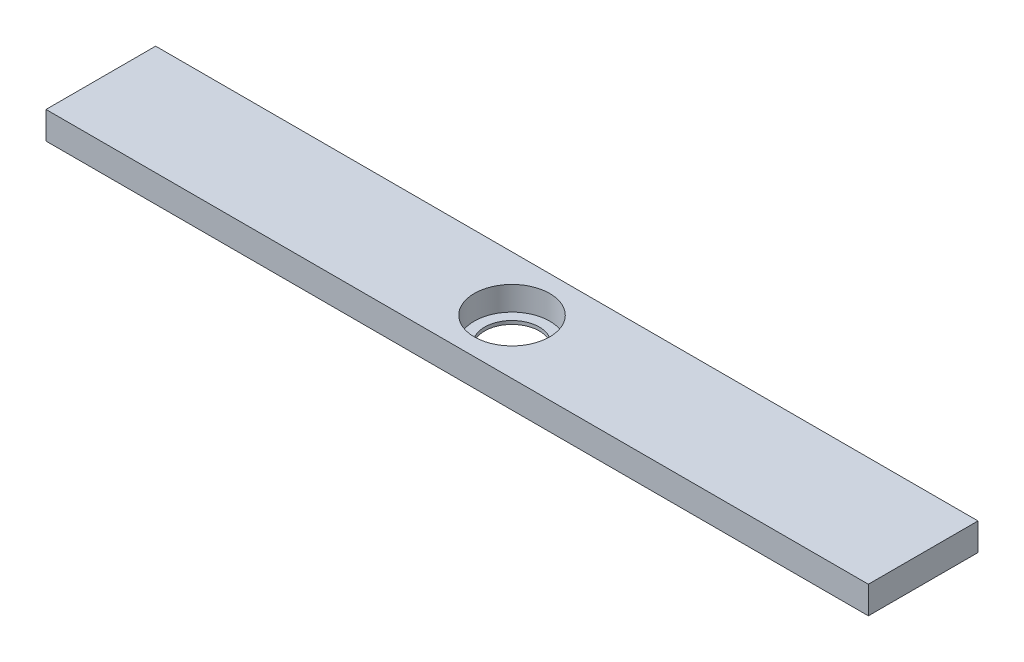
SolidWorks part; units mm, degrees
material "6061-T6 (SS)"
ref_plane "Front Plane" through (0, 0, 0) normal (0, 0, 1) x (1, 0, 0)
ref_plane "Top Plane" through (0, 0, 0) normal (0, 1, 0) x (1, 0, 0)
ref_plane "Right Plane" through (0, 0, 0) normal (1, 0, 0) x (0, 0, -1)
sketch "Sketch1" plane through (0, 0, 0) normal (0, 1, 0) x (1, 0, 0)
  line L1 (-190.5, -25.4) -> (190.5, -25.4)
  line L2 (-190.5, -25.4) -> (-190.5, 25.4)
  line L3 (-190.5, 25.4) -> (190.5, 25.4)
  line L4 (190.5, -25.4) -> (190.5, 25.4)
  line L5 (-190.5, -25.4) -> (190.5, 25.4) construction
  line L6 (-190.5, 25.4) -> (190.5, -25.4) construction
  point P0 (0, 0)
  dimension "D1" = 381
  dimension "D2" = 50.8
extrude "Boss-Extrude1" add sketch "Sketch1" along normal blind 12.7
sketch "Sketch2" plane through (0, 12.7, 0) normal (0, 1, 0) x (1, 0, 0)
  circle A0 centre (0, 0) radius 17.4625
  dimension "D1" = 34.925
extrude "Cut-Extrude1" cut sketch "Sketch2" against normal blind 11.1125
sketch "Sketch3" plane through (0, 1.5875, 0) normal (0, 1, 0) x (1, 0, 0)
  circle A0 centre (0, 0) radius 12.7
  dimension "D1" = 25.4
extrude "Cut-Extrude2" cut sketch "Sketch3" against normal through all
